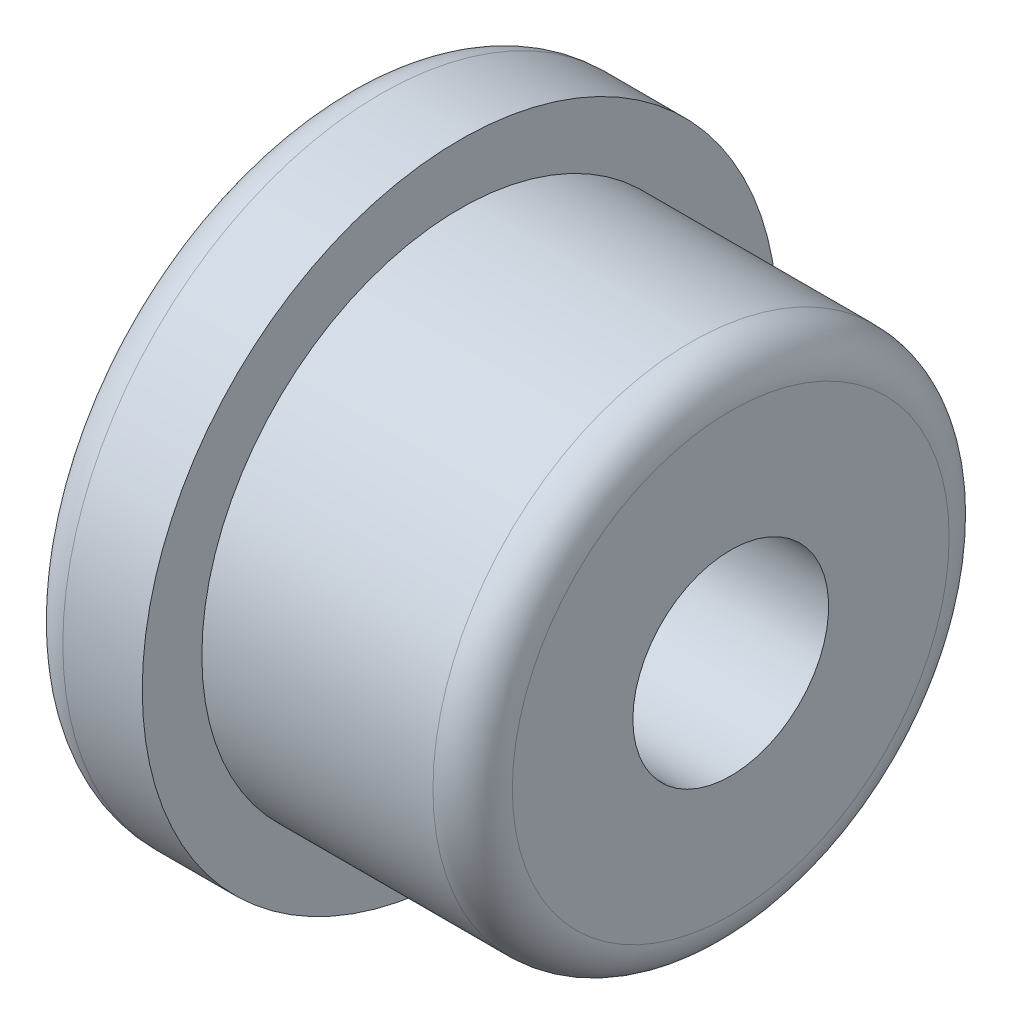
SolidWorks part; units mm, degrees
ref_plane "Alzado" through (0, 0, 0) normal (0, 0, 1) x (1, 0, 0)
ref_plane "Planta" through (0, 0, 0) normal (0, 1, 0) x (1, 0, 0)
ref_plane "Vista lateral" through (0, 0, 0) normal (1, 0, 0) x (0, 0, -1)
sketch "Croquis1" plane through (0, 0, 0) normal (0, 0, 1) x (1, 0, 0)
  line L0 (0, 0) -> (9.82, 0) construction
  line L1 (0, 2.465) -> (9.82, 2.465)
  line L2 (9.82, 2.465) -> (9.82, 6.5)
  line L3 (9.82, 6.5) -> (3, 6.5)
  line L4 (3, 6.5) -> (3, 8)
  line L5 (3, 8) -> (0, 8)
  line L6 (0, 8) -> (0, 2.465)
  point P5 (0, 0)
  dimension "D1" = 9.82
  dimension "D2" = 4.93
  dimension "D3" = 13
  dimension "D4" = 16
  dimension "D5" = 3
revolve "Revolución1" add sketch "Croquis1" angle 360 about L0
fillet "Redondeo1" radius 1 2 edges at (9.82, 0, 6.5) (0, 0, 8)
